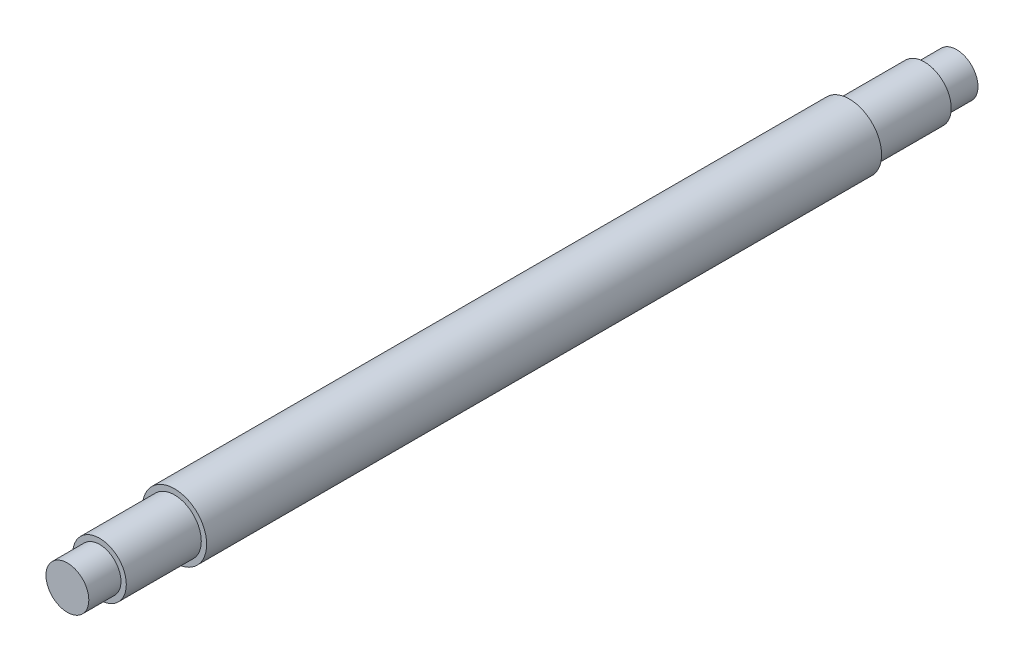
SolidWorks part; units mm, degrees
ref_plane "Front" through (0, 0, 0) normal (0, 0, 1) x (1, 0, 0)
ref_plane "Top" through (0, 0, 0) normal (0, 1, 0) x (1, 0, 0)
ref_plane "Right" through (0, 0, 0) normal (1, 0, 0) x (0, 0, -1)
sketch "Sketch1" plane through (0, 0, 0) normal (1, 0, 0) x (0, 0, -1)
  line L0 (-10.0733, 0) -> (92.1223, 0) construction
  line L1 (0, 0) -> (0, 2)
  line L2 (3, 2.5) -> (10, 2.5)
  line L3 (10, 2.5) -> (10, 3)
  line L4 (10, 3) -> (73, 3)
  line L5 (73, 3) -> (73, 2.5)
  line L6 (73, 2.5) -> (80, 2.5)
  line L7 (83, 2) -> (83, 0)
  line L8 (83, 0) -> (0, 0)
  line L9 (3, 2.5) -> (3, 2)
  line L10 (3, 2) -> (0, 2)
  line L11 (80, 2.5) -> (80, 2)
  line L12 (80, 2) -> (83, 2)
  dimension "D1" = 5
  dimension "D2" = 6
  dimension "D3" = 83
  dimension "D4" = 10
  dimension "D5" = 3
  dimension "D6" = 4
revolve "Revolve1" add sketch "Sketch1" angle 360 about L0
cosmetic thread "Cosmetic Thread1" parameters "D2"=3.22
cosmetic thread "Cosmetic Thread2" parameters "D2"=3.22
